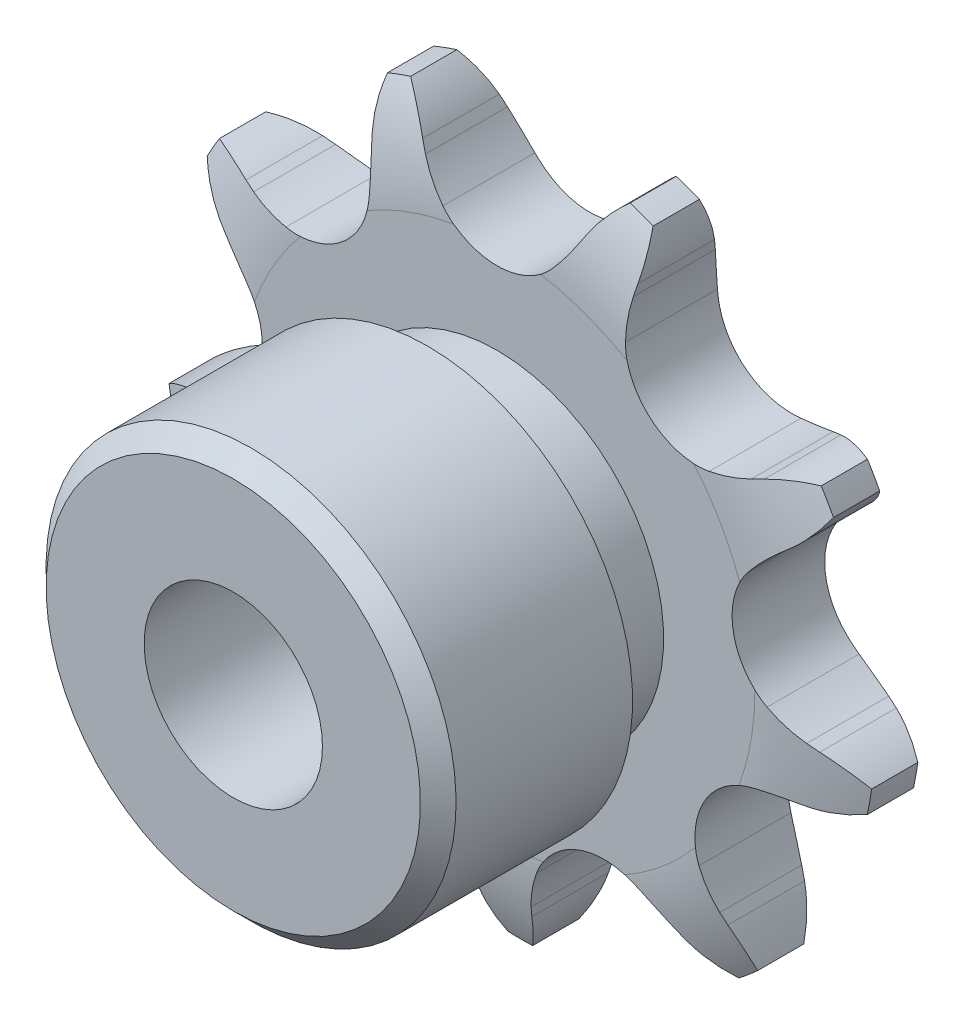
SolidWorks part; units mm, degrees
ref_plane "Front Plane" through (0, 0, 0) normal (0, 0, 1) x (1, 0, 0)
ref_plane "Top Plane" through (0, 0, 0) normal (0, 1, 0) x (1, 0, 0)
ref_plane "Right Plane" through (0, 0, 0) normal (1, 0, 0) x (0, 0, -1)
sketch "Sketch0" plane through (0, 0, 0) normal (0, 0, 1) x (1, 0, 0)
  line L0 (3, -8.2424) -> (0, 0) construction
  line L1 (0, 0) -> (7.5963, -4.3857) construction
  line L2 (0, 0) -> (-3, -8.2424) construction
  line L3 (3, -8.2424) -> (7.5963, -4.3857) construction
  line L4 (3, -8.2424) -> (-3, -8.2424) construction
  line L5 (5.0985, -7.2441) -> (4.8625, -7.0453)
  line L6 (3, -8.2424) -> (0, -9.3343) construction
  line L7 (0.7508, -8.8266) -> (0.8038, -8.5226)
  line L8 (0, -8.2424) -> (0, -10.0424) construction
  line L9 (3.972, -6.4397) -> (1.4813, -11.0591) construction
  line L10 (0, 0) -> (0, -8.2424) construction
  line L11 (4.8625, -7.0453) -> (1.4813, -11.0591) construction
  line L12 (0, -10.0424) -> (0, -10.4354) construction
  line L13 (7.2898, -4.6428) -> (5.0985, -7.2441) construction
  circle A0 centre (0, 0) radius 10.0424 construction
  circle A1 centre (0, 0) radius 8.7714 construction
  arc A2 (-3.6232, -11.4862) -> (10.1587, -6.47) centre (0, 0) ccw
  circle A3 centre (0, 0) radius 10.4354 construction
  circle A4 centre (3, -8.2424) radius 2 construction
  arc A7 (3.972, -6.4397) -> (1.0966, -7.4863) centre (3, -8.2424) ccw
  circle A8 centre (3, -8.2424) radius 2.0481 construction
  arc A9 (5.0985, -7.2441) -> (10.1587, -6.47) centre (7.2898, -4.6428) ccw
  arc A10 (4.8625, -7.0453) -> (3.972, -6.4397) centre (1.4813, -11.0591) ccw
  arc A11 (0.7508, -8.8266) -> (-3.6232, -11.4862) centre (-2.6, -8.2424) cw
  arc A12 (0.8038, -8.5226) -> (1.0966, -7.4863) centre (5.9739, -9.4239) cw
  dimension "D1" = 2.0481
  dimension "Dr" = 4
  dimension "Ds" = 4.0962
  dimension "R" = 2.0481
  dimension "Pitch" = 6
  dimension "A" = 41.667
  dimension "360/N" = 40
  dimension "B" = 11.778
  dimension "ab" = 5.6
  dimension "J" = 1.8
  dimension "ac" = 3.2
sketch "Sketch1" plane through (0, 0, 0) normal (1, 0, 0) x (0, 0, -1)
  line L0 (1.3, 0) -> (-1.3, 0)
  line L1 (-1.3, 0) -> (-1.3, 7.23)
  line L2 (-1.3, 8.7714) -> (0, 8.7714) construction
  line L3 (-0.6, 10.0424) -> (0.6, 10.0424)
  line L5 (1.3, 7.23) -> (1.3, 0)
  line L7 (0, 10.0424) -> (0, 0) construction
  line L8 (-1.3, 7.23) -> (1.3, 7.23) construction
  line L9 (0, 10.0424) -> (0, -10.0424) construction
  line L10 (-1.3, 7.23) -> (-1.3, 10.0424) construction
  line L11 (-1.3, 10.0424) -> (-0.6, 10.0424) construction
  line L12 (0.6, 10.0424) -> (1.3, 10.0424) construction
  line L13 (1.3, 10.0424) -> (1.3, 7.23) construction
  line L14 (0, 0) -> (-6.4008, 0) construction
  line L15 (-1.3, 8.7714) -> (-1.3, 4.6714) construction
  line L22 (1.3, 0) -> (-8.7, 0) construction
  line L24 (-1.3, 0) -> (-1.3, 4.6714) construction
  arc A0 (-0.6, 10.0424) -> (-1.3, 7.23) centre (4.7, 7.23) ccw
  arc A1 (0.6, 10.0424) -> (1.3, 7.23) centre (-4.7, 7.23) cw
  dimension "R" = 6
  dimension "t" = 2.6
  dimension "C" = 0.7
  dimension "A" = 2.8125
  dimension "K" = 6.4008
  dimension "Width" = 10
  dimension "H" = 4.1
revolve "Revolve1" add sketch "Sketch1" angle 360 about L0
extrude "Cut-Extrude1" cut sketch "Sketch0" against normal through all and the other way through all
pattern_circular "CirPattern1" count 9 over 360 about axis through (0, 0, 0) along (0, 0, 1) of "Cut-Extrude1"
sketch "Sketch2" plane through (0, 0, 0) normal (0, 0, 1) x (1, 0, 0)
  circle A0 centre (0, 0) radius 2.5 construction
  circle A1 centre (0, 0) radius 5.75
  circle A2 centre (0, 0) radius 9.95 construction
  dimension "Bore" = 5
  dimension "Hub Dia." = 11.5
  dimension "OD" = 19.9
extrude "Boss-Extrude1" add sketch "Sketch2" along normal up to vertex (8.7 mm away) from surface at 1.3 starting at face at (0, 0, 1.3)
sketch "Sketch3" plane through (0, 0, 0) normal (0, 0, 1) x (1, 0, 0)
  circle A0 centre (0, 0) radius 2.5 construction
  circle A1 centre (0, 0) radius 2.5
extrude "Cut-Extrude2" cut sketch "Sketch3" along normal through all and the other way through all
sketch "Sketch4" plane through (0, 0, 0) normal (1, 0, 0) x (0, 0, -1)
  line L0 (-8.7, 5.75) -> (-8.7, 5.25)
  line L1 (-1.3, 10.0424) -> (-3.25, 10.0424)
  line L2 (-1.3, 10.0424) -> (-1.3, 4.6714)
  line L3 (-1.3, 4.6714) -> (-3.25, 4.6714)
  line L4 (-3.25, 10.0424) -> (-3.25, 4.6714)
  line L9 (-8.7, 5.25) -> (-8.2, 5.75)
  line L10 (-8.2, 5.75) -> (-8.7, 5.75)
  dimension "C" = 0.5
  dimension "D3" = 1.95
revolve "Cut-Revolve1" cut sketch "Sketch4" angle 360 about L22
sketch "Sketch5" plane through (0, 0, 0) normal (0, 0, 1) x (1, 0, 0)
  circle A0 centre (0, 0) radius 9.95 construction
  circle A1 centre (0, 0) radius 9.95
extrude "Cut-Extrude3" cut sketch "Sketch5" against normal through all and the other way through all flip side to cut
equation "\"360/N@Sketch0\" = 360/\"Teeth@CirPattern1\""
equation "\"Ds@Sketch0\" = 1.005 * \"Dr@Sketch0\" + ( 0.003 * 25.4 ) "
equation "\"R@Sketch0\" = 1/2 * \"Ds@Sketch0\""
equation "\"A@Sketch0\" = 35 +  ( 60 / \"Teeth@CirPattern1\" ) "
equation "\"B@Sketch0\" = 18 -  ( 56 / \"Teeth@CirPattern1\" )"
equation "\"ac@Sketch0\" = 0.8 * \"Dr@Sketch0\""
equation "\"ab@Sketch0\" = 1.4 * \"Dr@Sketch0\""
equation "\"J@Sketch0\" = 0.3 * \"Pitch@Sketch0\""
equation "\"D3@Sketch4\" = \"t@Sketch1\" * 3 / 4"
